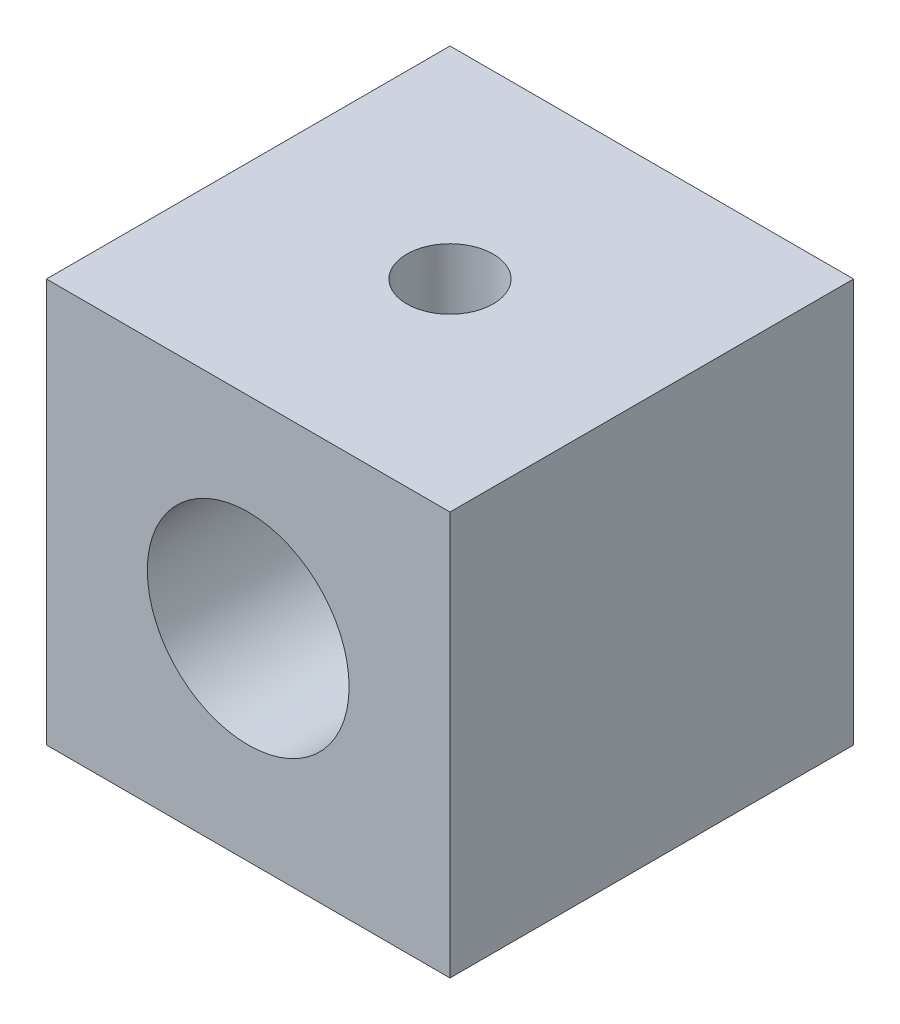
SolidWorks part; units mm, degrees
ref_plane "Alzado" through (0, 0, 0) normal (0, 0, 1) x (1, 0, 0)
ref_plane "Planta" through (0, 0, 0) normal (0, 1, 0) x (1, 0, 0)
ref_plane "Vista lateral" through (0, 0, 0) normal (1, 0, 0) x (0, 0, -1)
sketch "Croquis1" plane through (0, 0, 0) normal (0, 0, 1) x (1, 0, 0)
  line L1 (20, 20) -> (-20, 20)
  line L2 (20, 20) -> (20, -20)
  line L3 (20, -20) -> (-20, -20)
  line L4 (-20, 20) -> (-20, -20)
  line L5 (20, 20) -> (-20, -20) construction
  line L6 (20, -20) -> (-20, 20) construction
  circle A0 centre (0, 0) radius 10
  dimension "D1" = 20
  dimension "D2" = 40
  dimension "D3" = 40
extrude "Saliente-Extruir1" add sketch "Croquis1" along normal blind 40
sketch "Croquis3" plane through (0, -20, 0) normal (0, -1, 0) x (1, 0, 0)
  circle A0 centre (0, 20) radius 4.2836
extrude "Cortar-Extruir1" cut sketch "Croquis3" against normal through all
